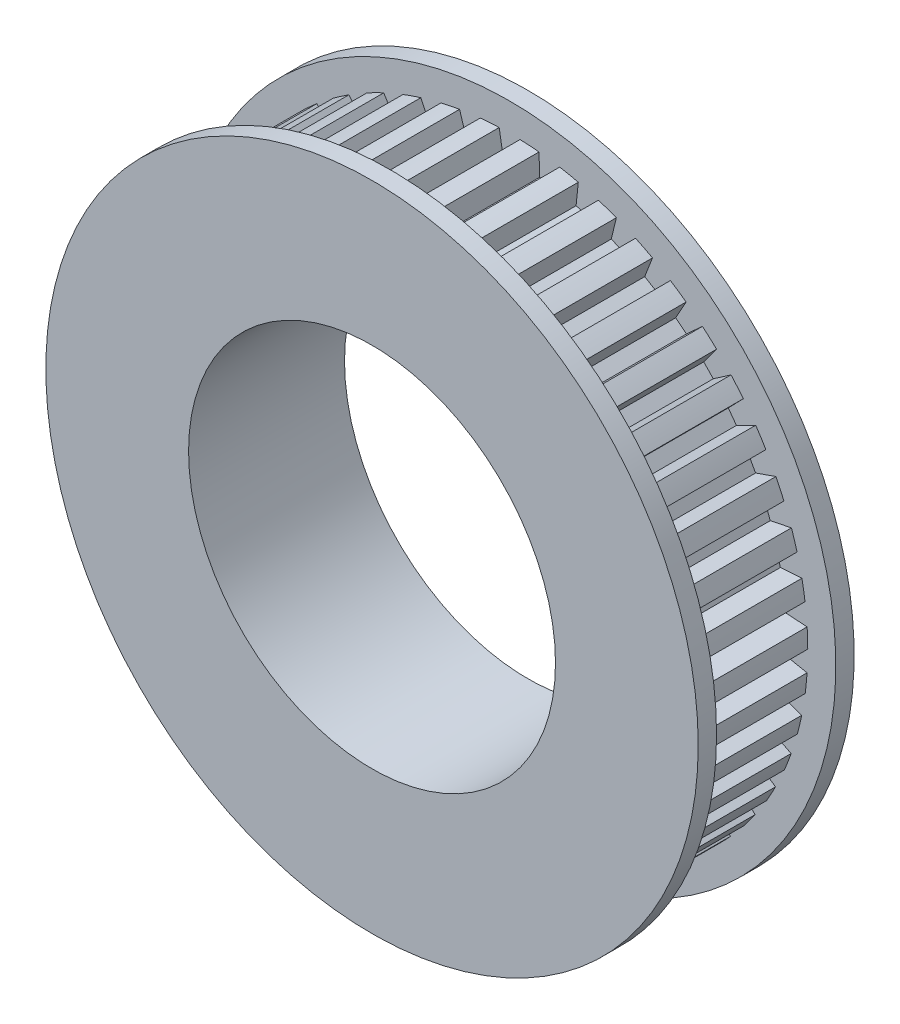
SolidWorks part; units mm, degrees
ref_plane "Front Plane" through (0, 0, 0) normal (0, 0, 1) x (1, 0, 0)
ref_plane "Top Plane" through (0, 0, 0) normal (0, 1, 0) x (1, 0, 0)
ref_plane "Right Plane" through (0, 0, 0) normal (1, 0, 0) x (0, 0, -1)
sketch "Sketch3" plane through (0, 0, 0) normal (0, 0, 1) x (1, 0, 0)
  circle A0 centre (0, 0) radius 16.25
  dimension "D1" = 32.5
extrude "Boss-Extrude2" add sketch "Sketch3" along normal mid plane 6.5
sketch "Sketch1" plane through (0, 0, 0) normal (0, 0, 1) x (1, 0, 0)
  line L0 (-0.375, 15.08) -> (0.375, 15.08)
  line L2 (-0.375, 15.08) -> (-0.6543, 16.7561)
  line L3 (-0.6543, 16.7561) -> (0.6543, 16.7561)
  line L4 (0.6543, 16.7561) -> (0.375, 15.08)
  line L5 (-0.5, 15.83) -> (0.5, 15.83) construction
  point P9 (0, 16.7561)
  point P10 (0, 15.08)
  dimension "D1" = 0.75
  dimension "D2" = 0.75
  dimension "D3" = 1
  dimension "D4" = 15.08
extrude "Cut-Extrude2" cut sketch "Sketch1" against normal through all both and the other way through all
pattern_circular "CirPattern3" count 47 over 360 about axis through (0, 0, 0) along (0, 0, 1) of "Cut-Extrude2"
sketch "Sketch5" plane through (0, 0, -3.25) normal (0, 0, -1) x (-1, 0, 0)
  circle A0 centre (0, 0) radius 17.78
  dimension "D1" = 35.56
extrude "Boss-Extrude3" add sketch "Sketch5" along normal blind 1
sketch "Sketch6" plane through (0, 0, 3.25) normal (0, 0, 1) x (1, 0, 0)
  circle A0 centre (0, 0) radius 17.78
  dimension "D1" = 35.56
extrude "Boss-Extrude4" add sketch "Sketch6" along normal blind 1
sketch "Sketch7" plane through (0, 0, 4.25) normal (0, 0, 1) x (1, 0, 0)
  circle A0 centre (0, 0) radius 10
  dimension "D1" = 20
extrude "Cut-Extrude3" cut sketch "Sketch7" against normal through all both and the other way through all
